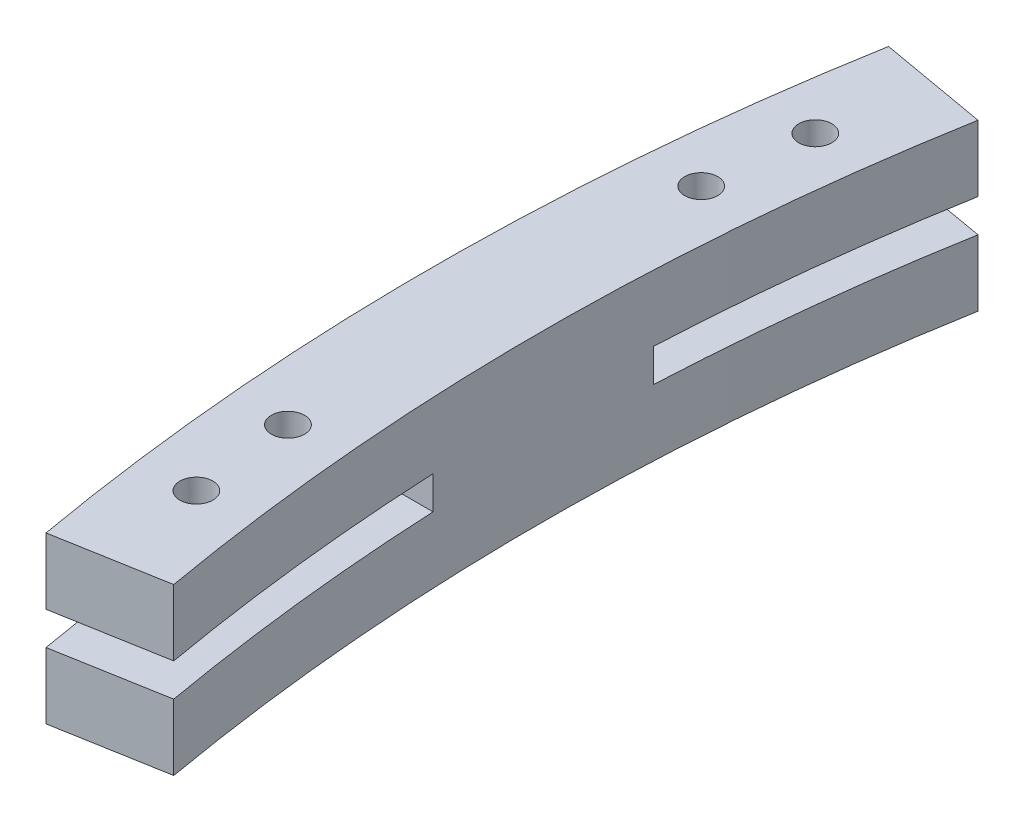
SolidWorks part; units mm, degrees
ref_plane "Front Plane" through (0, 0, 0) normal (0, 0, 1) x (1, 0, 0)
ref_plane "Top Plane" through (0, 0, 0) normal (0, 1, 0) x (1, 0, 0)
ref_plane "Right Plane" through (0, 0, 0) normal (1, 0, 0) x (0, 0, -1)
sketch "Sketch1" plane through (0, 0, 0) normal (0, 0, 1) x (1, 0, 0)
  line L0 (190, 0) -> (-190, 0) construction
  line L1 (0, 190) -> (0, -190) construction
  line L2 (0, 0) -> (-187.1135, 32.9932) construction
  line L3 (0, 0) -> (-187.1135, -32.9932) construction
  line L4 (-187.1135, 32.9932) -> (-196.9616, 34.7296)
  line L5 (-187.1135, -32.9932) -> (-196.9616, -34.7296)
  arc A0 (-187.1135, 32.9932) -> (-187.1135, -32.9932) centre (0, 0) ccw
  arc A1 (-196.9616, 34.7296) -> (-196.9616, -34.7296) centre (0, 0) ccw
  circle A3 centre (0, 0) radius 190 construction
  dimension "D1" = 380
  dimension "D2" = 10
  dimension "D3" = 20
sketch "Sketch9" plane through (0, 0, 0) normal (0, 1, 0) x (1, 0, 0)
  line L0 (0, 0) -> (-196.9616, 34.7296)
  line L1 (-200, 0) -> (200, 0) construction
  line L2 (0, 0) -> (-196.9616, -34.7296)
  circle A0 centre (0, 0) radius 195 construction
  circle A1 centre (0, 0) radius 195 construction
  circle A8 centre (0, 0) radius 200 construction
  circle A9 centre (0, 0) radius 190 construction
  circle A10 centre (0, 0) radius 200
  circle A11 centre (0, 0) radius 190
  dimension "D1" = 20
extrude "base" [suppressed] add sketch "Sketch9" along normal mid plane 15 contours A11 L0 A10 L2
sketch "Sketch11" [suppressed] plane through (0, 0, 0) normal (0, 1, 0) x (1, 0, 0)
  line L8 (-189.7367, -10) -> (-199.7498, -10) construction
  line L9 (-187.1135, -32.9932) -> (-196.9616, -34.7296) construction
  line L10 (-189.7367, 10) -> (-199.7498, 10) construction
  line L11 (-187.1135, 32.9932) -> (-196.9616, 34.7296) construction
  line L12 (-189.7367, -10) -> (-199.7498, -10)
  line L13 (-187.1135, -32.9932) -> (-196.9616, -34.7296)
  line L14 (-189.7367, 10) -> (-199.7498, 10)
  line L15 (-187.1135, 32.9932) -> (-196.9616, 34.7296)
  circle A14 centre (0, 0) radius 200 construction
  circle A15 centre (0, 0) radius 190 construction
  arc A16 (-196.9616, 34.7296) -> (-199.7498, 10) centre (0, 0) ccw
  arc A17 (-187.1135, 32.9932) -> (-189.7367, 10) centre (0, 0) ccw
  arc A18 (-199.7498, -10) -> (-196.9616, -34.7296) centre (0, 0) ccw
  arc A19 (-189.7367, -10) -> (-187.1135, -32.9932) centre (0, 0) ccw
extrude "Cut-Extrude8" [suppressed] cut sketch "Sketch11" along normal up to surface and the other way up to surface
sketch "Sketch12" plane through (0, 0, 0) normal (0, 1, 0) x (1, 0, 0)
  line L0 (-200, 0) -> (200, 0) construction
  line L1 (-200, 0) -> (200, 0) construction
  circle A0 centre (0, 0) radius 195 construction
  circle A1 centre (0, 0) radius 195 construction
  circle A2 centre (-193.3908, 25) radius 1.5
  circle A3 centre (-194.4222, 15) radius 1.5
  circle A4 centre (-194.4222, -15) radius 1.5
  circle A5 centre (-193.3908, -25) radius 1.5
  dimension "D1" = 3
  dimension "D2" = 30
  dimension "D3" = 50
extrude "Cut-Extrude9" [suppressed] cut sketch "Sketch12" against normal through all both and the other way through all
sketch "Sketch13" plane through (0, 0, 0) normal (0, 1, 0) x (1, 0, 0)
  line L2 (0, 0) -> (-216.6577, 38.2026)
  line L4 (-215, 0) -> (215, 0) construction
  line L5 (-215, 0) -> (215, 0) construction
  line L6 (0, 0) -> (-216.6577, -38.2026)
  line L7 (-209.7618, -10) -> (-219.7726, -10) construction
  line L8 (-209.7618, 10) -> (-219.7726, 10) construction
  line L9 (-209.7618, -10) -> (-219.7726, -10)
  line L10 (-209.7618, 10) -> (-219.7726, 10)
  circle A5 centre (0, 0) radius 215 construction
  circle A6 centre (0, 0) radius 220 construction
  circle A7 centre (0, 0) radius 210 construction
  circle A8 centre (0, 0) radius 220
  circle A9 centre (0, 0) radius 210
  dimension "D1" = 20
extrude "base2" add sketch "Sketch13" along normal mid plane 15 contours A9 L2 A8 L10 | A9 L10 A8 L9 | A9 L9 A8 L6
sketch "Sketch14" plane through (0, 0, 0) normal (0, 1, 0) x (1, 0, 0)
  line L0 (-209.7618, -10) -> (-219.7726, -10) construction
  line L1 (-209.7618, 10) -> (-219.7726, 10) construction
  line L2 (-209.7618, -10) -> (-219.7726, -10)
  line L3 (-209.7618, 10) -> (-219.7726, 10)
  line L4 (0, 0) -> (-216.6577, 38.2026) construction
  line L5 (0, 0) -> (-216.6577, -38.2026) construction
  line L6 (-206.8096, 36.4661) -> (-216.6577, 38.2026)
  line L7 (-206.8096, -36.4661) -> (-216.6577, -38.2026)
  arc A0 (-219.7726, -10) -> (-216.6577, -38.2026) centre (0, 0) ccw
  arc A1 (-209.7618, -10) -> (-206.8096, -36.4661) centre (0, 0) ccw
  circle A4 centre (0, 0) radius 220 construction
  circle A5 centre (0, 0) radius 210 construction
  arc A6 (-216.6577, 38.2026) -> (-219.7726, 10) centre (0, 0) ccw
  arc A7 (-206.8096, 36.4661) -> (-209.7618, 10) centre (0, 0) ccw
extrude "mount2" cut sketch "Sketch14" along normal up to surface and the other way up to surface
sketch "Sketch16" plane through (0, 0, 0) normal (0, 1, 0) x (1, 0, 0)
  line L0 (-214.1819, 18.7385) -> (0, 0) construction
  line L1 (0, 0) -> (-213.1606, 28.0631) construction
  line L3 (0, 0) -> (-215, 0) construction
  line L4 (-214.1819, -18.7385) -> (0, 0) construction
  line L5 (0, 0) -> (-213.1606, -28.0631) construction
  circle A0 centre (0, 0) radius 215 construction
  circle A1 centre (0, 0) radius 215 construction
  circle A2 centre (-213.1606, 28.0631) radius 1.5
  circle A3 centre (-214.1819, 18.7385) radius 1.5
  circle A4 centre (-214.1819, -18.7385) radius 1.5
  circle A5 centre (-213.1606, -28.0631) radius 1.5
  dimension "D1" = 3
  dimension "D2" = 10
  dimension "D3" = 15
extrude "mount hole2" cut sketch "Sketch16" against normal through all both and the other way through all
ref_plane "shaft" through (-215, 0, 0) normal (1, 0, 0) x (0, 0, -1)
sketch "Sketch17" plane through (-215, 0, 0) normal (1, 0, 0) x (0, 0, -1)
  circle A0 centre (0, 0) radius 1.5
  dimension "D1" = 3
sketch "Sketch18" plane through (0, 0, 0) normal (0, 1, 0) x (1, 0, 0)
  line L6 (-213.75, 3) -> (-216.25, 3) construction
  line L7 (-213.75, 3) -> (-213.75, -3) construction
  line L8 (-213.75, -3) -> (-216.25, -3) construction
  line L9 (-216.25, 3) -> (-216.25, -3) construction
  line L10 (-213.75, 3) -> (-216.25, -3) construction
  line L11 (-213.75, -3) -> (-216.25, 3) construction
  line L12 (-216.25, 3) -> (-213.75, 3)
  line L13 (-216.25, 3) -> (-216.25, 0)
  line L14 (-216.25, 0) -> (-213.75, 0)
  line L15 (-213.75, 3) -> (-213.75, 0)
  point P0 (-215, 0)
  dimension "D1" = 6
  dimension "D2" = 2.5
revolve "bearing" cut sketch "Sketch18" angle 360 about L5
sketch "Sketch6" plane through (0, 0, 0) normal (0, 0, 1) x (1, 0, 0)
  line L1 (-208.5097, 7.5) -> (-171.4903, 7.5)
  line L2 (-208.5097, 7.5) -> (-208.5097, -7.5)
  line L3 (-208.5097, -7.5) -> (-171.4903, -7.5)
  line L4 (-171.4903, 7.5) -> (-171.4903, -7.5)
  line L5 (-208.5097, 7.5) -> (-171.4903, -7.5) construction
  line L6 (-208.5097, -7.5) -> (-171.4903, 7.5) construction
  arc A0 (-196.9616, 34.7296) -> (-196.9616, -34.7296) centre (0, 0) ccw construction
  arc A1 (-187.1135, 32.9932) -> (-187.1135, -32.9932) centre (0, 0) ccw construction
  arc A2 (-196.9616, 34.7296) -> (-196.9616, -34.7296) centre (0, 0) ccw
  arc A3 (-187.1135, 32.9932) -> (-187.1135, -32.9932) centre (0, 0) ccw
  point P0 (-190, 0)
  dimension "D1" = 15
ref_plane "Plane1" through (-190, 0, 0) normal (1, 0, 0) x (0, 0, -1)
sketch "Sketch4" plane through (-190, 0, 0) normal (1, 0, 0) x (0, 0, -1)
  circle A0 centre (0, 0) radius 3
  dimension "D1" = 6
sketch "Sketch7" plane through (-190, 0, 0) normal (1, 0, 0) x (0, 0, -1)
  circle A0 centre (0, 0) radius 1.5
  dimension "D1" = 3
ref_plane "Plane2" through (-215, 0, 0) normal (1, 0, 0) x (0, 0, -1)
sketch "Sketch19" plane through (-215, 0, 0) normal (1, 0, 0) x (0, 0, -1)
  circle A0 centre (0, 0) radius 1.5
  dimension "D1" = 3
extrude "Cut-Extrude10" cut sketch "Sketch19" against normal through all
